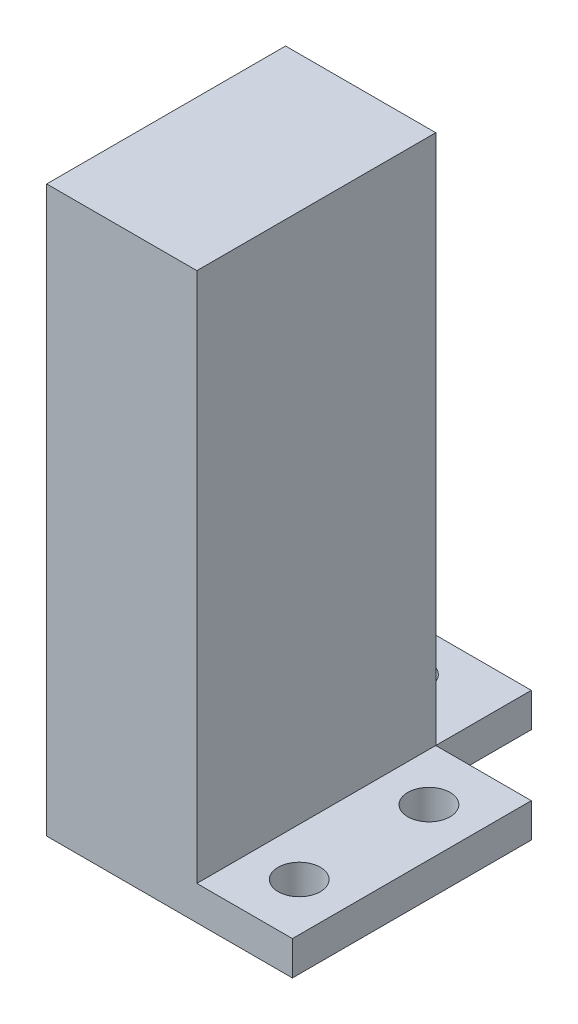
SolidWorks part; units mm, degrees
ref_plane "Front Plane" through (0, 0, 0) normal (0, 0, 1) x (1, 0, 0)
ref_plane "Top Plane" through (0, 0, 0) normal (0, 1, 0) x (1, 0, 0)
ref_plane "Right Plane" through (0, 0, 0) normal (1, 0, 0) x (0, 0, -1)
sketch "Sketch1" plane through (0, 0, 0) normal (0, 0, 1) x (1, 0, 0)
  line L0 (-11, 49.2197) -> (-11, -33.5303)
  line L2 (11, 49.2197) -> (11, -33.5303)
  line L3 (11, 49.2197) -> (-11, 49.2197)
  line L5 (-11, -33.5303) -> (11, -33.5303)
  circle A0 centre (0, 35.7197) radius 3.1
  circle A1 centre (0, 7.7197) radius 3.1
  dimension "D1" = 13.5
  dimension "D2" = 28
  dimension "D3" = 82.75
extrude "Boss-Extrude1" add sketch "Sketch1" along normal blind 30
sketch "Sketch2" plane through (0, 0, 30) normal (0, 0, 1) x (1, 0, 0)
  line L0 (-11, -33.5303) -> (11, -33.5303) construction
  line L2 (11, 49.2197) -> (-11, 49.2197) construction
  line L4 (-11, -33.5303) -> (11, -33.5303)
  line L5 (11, -33.5303) -> (11, 49.2197)
  line L6 (11, 49.2197) -> (-11, 49.2197)
  line L7 (-11, 49.2197) -> (-11, -33.5303)
extrude "Boss-Extrude2" add sketch "Sketch2" along normal blind 5
sketch "Sketch3" plane through (0, -33.5303, 0) normal (0, -1, 0) x (1, 0, 0)
  line L1 (-11, 0) -> (11, 0)
  line L2 (-11, 0) -> (-11, -14)
  line L3 (-11, -14) -> (11, -14)
  line L4 (11, 0) -> (11, -14)
  line L5 (11, 0) -> (25, 0)
  line L6 (11, 0) -> (11, 35)
  line L7 (11, 35) -> (25, 35)
  line L8 (25, 0) -> (25, 35)
  circle A0 centre (18, 8) radius 3.1
  circle A1 centre (18, 27) radius 3.1
  circle A2 centre (0, -7) radius 3.1
  line M3 (-11, 0) -> (11, 0)
  line M4 (11, 0) -> (11, 35)
  dimension "D3" = 6.2
  dimension "D4" = 6.2
  dimension "D5" = 6.2
  dimension "D7" = 8
  dimension "D8" = 11
  dimension "D1" = 14
  dimension "D2" = 14
  dimension "D6" = 8
extrude "Boss-Extrude3" add sketch "Sketch3" against normal blind 5 contours L4 L2 L3 A2 M3 | L5 L8 L7 A1 A0 M4
sketch "Sketch4" plane through (-11, 0, 0) normal (-1, 0, 0) x (0, 0, 1)
  line L6 (0, 49.2197) -> (0, -28.5303)
  line L7 (0, -28.5303) -> (-14, -28.5303)
  line L8 (-14, -28.5303) -> (-14, -33.5303)
  line L9 (-14, -33.5303) -> (35, -33.5303)
  line L10 (35, -33.5303) -> (35, 49.2197)
  line L11 (35, 49.2197) -> (0, 49.2197)
  line L12 (0, 49.2197) -> (0, -28.5303)
  line L13 (0, -28.5303) -> (-14, -28.5303)
  line L14 (-14, -28.5303) -> (-14, -33.5303)
  line L15 (-14, -33.5303) -> (35, -33.5303)
  line L16 (35, -33.5303) -> (35, 49.2197)
  line L17 (35, 49.2197) -> (0, 49.2197)
  dimension "D1" = 0
extrude "Boss-Extrude4" [suppressed] add sketch "Sketch4" along normal blind 2.5
sketch "Sketch5" plane through (0, 0, 30) normal (0, 0, -1) x (-1, 0, 0)
  circle A0 centre (0, 7.7197) radius 3.1
  circle A1 centre (0, 35.7197) radius 3.1
extrude "Boss-Extrude5" add sketch "Sketch5" along normal blind 15
